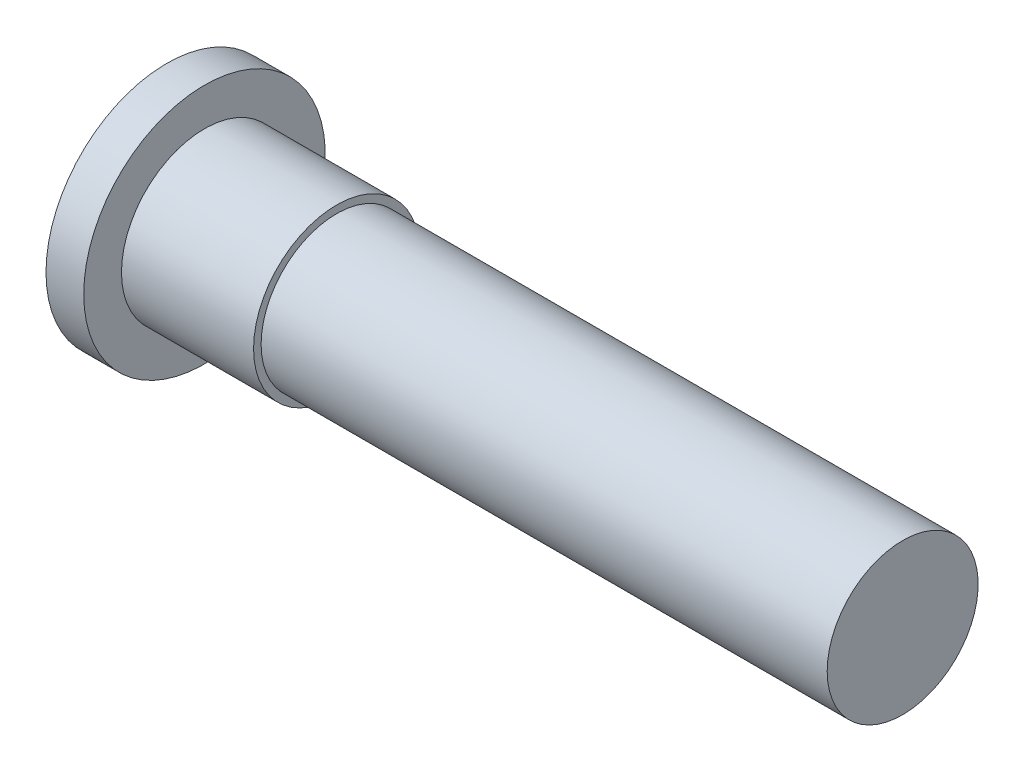
SolidWorks part; units mm, degrees
ref_plane "前视基准面" through (0, 0, 0) normal (0, 0, 1) x (1, 0, 0)
ref_plane "上视基准面" through (0, 0, 0) normal (0, 1, 0) x (1, 0, 0)
ref_plane "右视基准面" through (0, 0, 0) normal (1, 0, 0) x (0, 0, -1)
sketch "草图1" plane through (0, 0, 0) normal (0, 1, 0) x (1, 0, 0)
  line L0 (-110.7295, 0) -> (94.4829, 0) construction
  line L1 (0, 71.4319) -> (0, -43.7943) construction
  line L2 (0, 0) -> (0, 16)
  line L3 (0, 16) -> (5, 16)
  line L4 (5, 16) -> (5, 11)
  line L5 (5, 11) -> (22.5, 11)
  line L6 (97.5, 10) -> (97.5, 0)
  line L7 (0, 0) -> (97.5, 0)
  line L8 (22.5, 11) -> (22.5, 10)
  line L9 (22.5, 10) -> (97.5, 10)
revolve "旋转1" add sketch "草图1" angle 360 about L0
